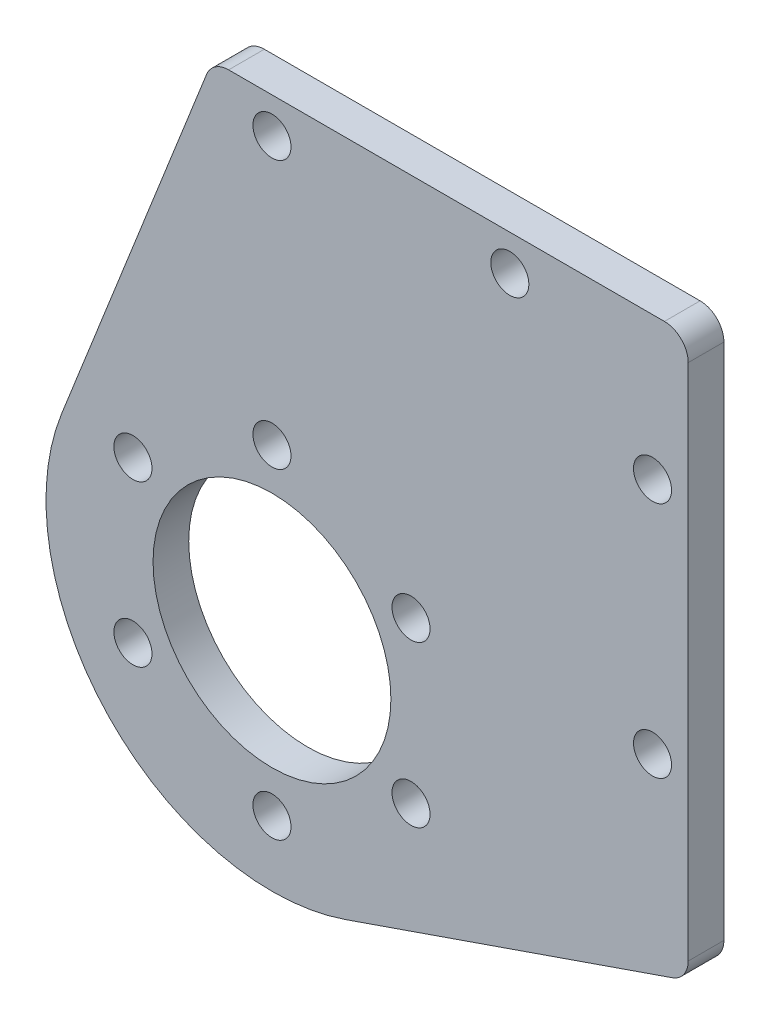
SolidWorks part; units mm, degrees
material "Thornel Mat VMA"
ref_plane "前视基准面" through (0, 0, 0) normal (0, 0, 1) x (1, 0, 0)
ref_plane "上视基准面" through (0, 0, 0) normal (0, 1, 0) x (1, 0, 0)
ref_plane "右视基准面" through (0, 0, 0) normal (1, 0, 0) x (0, 0, -1)
sketch "草图1" plane through (0, 0, 0) normal (0, 0, 1) x (1, 0, 0)
  circle A0 centre (0, 0) radius 10
  circle A1 centre (0, 0) radius 13.5 construction
  circle A2 centre (0, 13.5) radius 1.6
  circle A3 centre (0, 0) radius 19
  circle A4 centre (11.6913, 6.75) radius 1.6
  circle A5 centre (11.6913, -6.75) radius 1.6
  circle A6 centre (0, -13.5) radius 1.6
  circle A7 centre (-11.6913, -6.75) radius 1.6
  circle A8 centre (-11.6913, 6.75) radius 1.6
  point P19 (0, 0)
  dimension "D1" = 3.2
  dimension "D2" = 27
  dimension "D3" = 20
  dimension "D5" = 38
  dimension "D4" = 6
extrude "凸台-拉伸1" add sketch "草图1" along normal blind 3
sketch "草图2" plane through (0, 0, 3) normal (0, 0, 1) x (1, 0, 0)
  line L1 (35, -6.5754) -> (35, 37)
  line L2 (33, 39) -> (-3.6406, 39)
  line L3 (-5.5002, 37.7359) -> (-17.6669, 6.9914)
  line L4 (33.6537, -8.4656) -> (6.2099, -17.9565)
  circle A1 centre (32, 7) radius 1.6
  circle A2 centre (32, 27) radius 1.6
  circle A3 centre (0, 36) radius 1.6
  circle A4 centre (20, 36) radius 1.6
  circle A5 centre (0, 0) radius 19 construction
  arc A7 (6.2099, -17.9565) -> (-17.6669, 6.9914) centre (0, 0) ccw
  circle A8 centre (0, 0) radius 19 construction
  arc A10 (-3.6406, 39) -> (-5.5002, 37.7359) centre (-3.6406, 37) ccw
  arc A11 (35, 37) -> (33, 39) centre (33, 37) ccw
  arc A12 (35, -6.5754) -> (33.6537, -8.4656) centre (33, -6.5754) cw
  point P32 (-5, 39)
  point P35 (35, 39)
  point P41 (35, -8)
  dimension "D6" = 3.2
  dimension "D7" = 3.2
  dimension "D13" = 40
  dimension "D14" = 2
  dimension "D15" = 2
  dimension "D2" = 32
  dimension "D3" = 12
  dimension "D4" = 20
  dimension "D5" = 3
  dimension "D8" = 20
  dimension "D9" = 3
  dimension "D10" = 39
  dimension "D11" = 15
  dimension "D12" = 47
extrude "凸台-拉伸3" add sketch "草图2" against normal up to surface (3 mm away)
